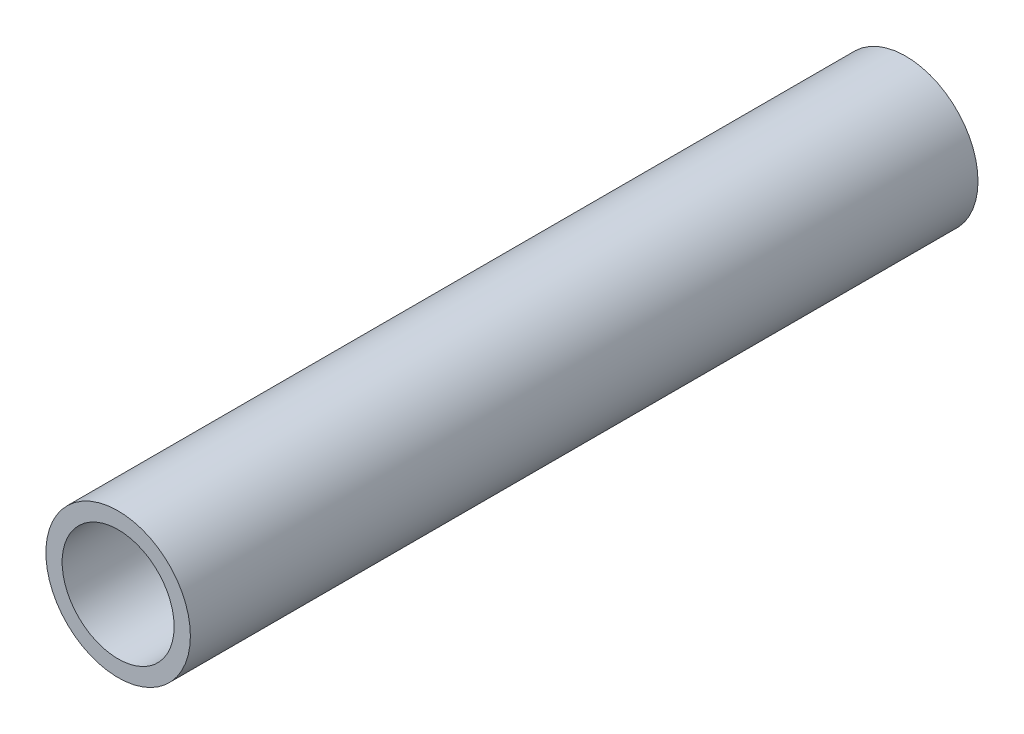
SolidWorks part; units mm, degrees
ref_plane "Спереди" through (0, 0, 0) normal (0, 0, 1) x (1, 0, 0)
ref_plane "Сверху" through (0, 0, 0) normal (0, 1, 0) x (1, 0, 0)
ref_plane "Справа" through (0, 0, 0) normal (1, 0, 0) x (0, 0, -1)
sketch "Эскиз1" plane through (0, 0, 0) normal (0, 0, 1) x (1, 0, 0)
  circle A0 centre (0, 0) radius 1
  circle A1 centre (0, 0) radius 0.775
extrude "Бобышка-Вытянуть1" add sketch "Эскиз1" along normal blind 10.9
